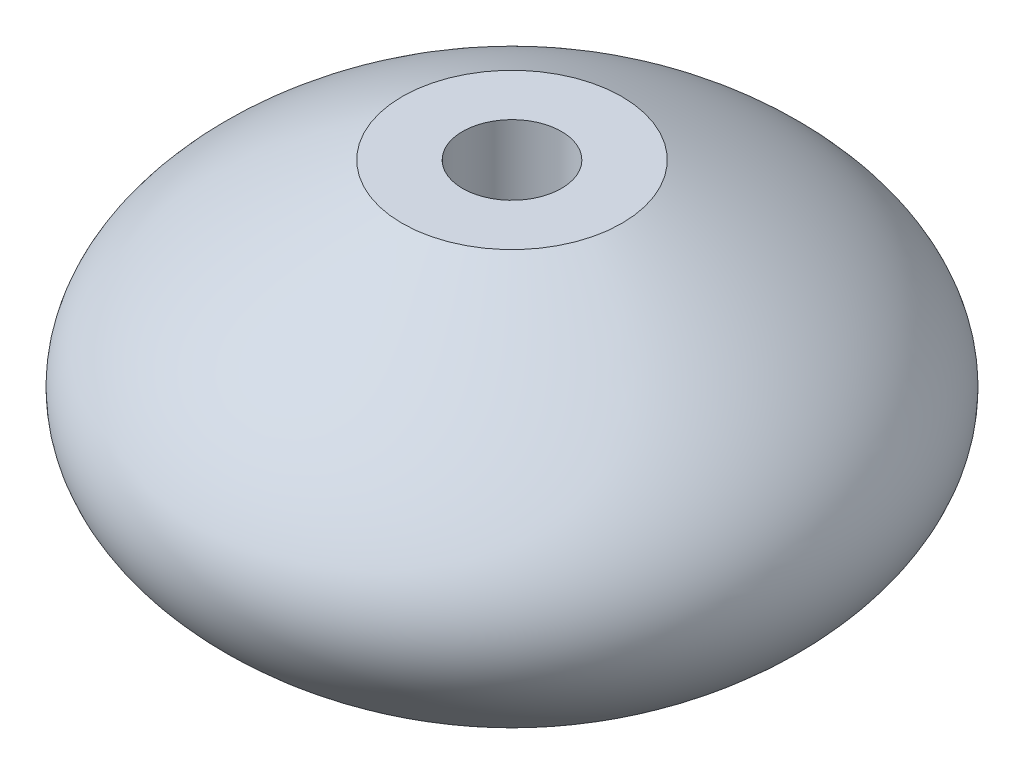
SolidWorks part; units mm, degrees
ref_plane "前视基准面" through (0, 0, 0) normal (0, 0, 1) x (1, 0, 0)
ref_plane "上视基准面" through (0, 0, 0) normal (0, 1, 0) x (1, 0, 0)
ref_plane "右视基准面" through (0, 0, 0) normal (1, 0, 0) x (0, 0, -1)
other "Configuration Table"
sketch "草图1" plane through (0, 0, 0) normal (0, 0, 1) x (1, 0, 0)
  line L4 (5, 8.95) -> (0, 8.95)
  line L5 (0, 8.95) -> (0, 0)
  line L6 (0, -8.95) -> (5, -8.95)
  line L7 (0, 0) -> (0, -8.95)
  spline S0 degree 2 poles (5, 8.95) (25, 0) (5, -8.95) knots 0 0 0 1 1 1
revolve "旋转1" add sketch "草图1" angle 360 about L5
sketch "草图2" plane through (0, 8.95, 0) normal (0, 1, 0) x (1, 0, 0)
  circle A0 centre (0, 0) radius 2.25
  dimension "D1" = 4.5
extrude "切除-拉伸1" cut sketch "草图2" against normal through all
